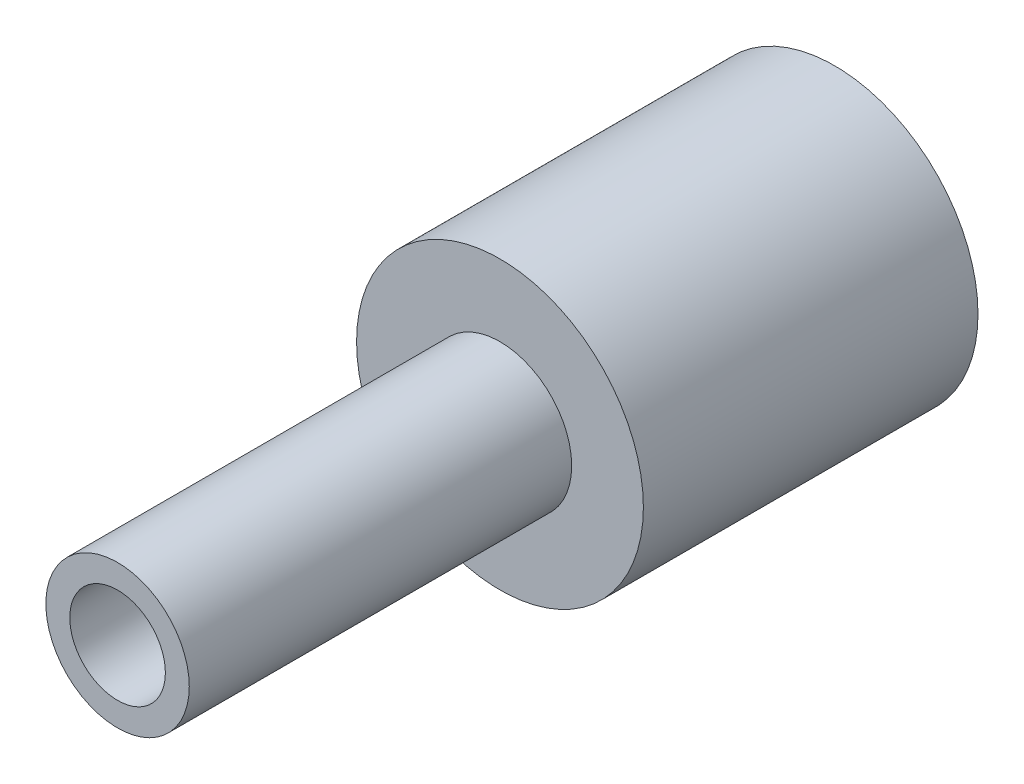
SolidWorks part; units mm, degrees
ref_plane "Front Plane" through (0, 0, 0) normal (0, 0, 1) x (1, 0, 0)
ref_plane "Top Plane" through (0, 0, 0) normal (0, 1, 0) x (1, 0, 0)
ref_plane "Right Plane" through (0, 0, 0) normal (1, 0, 0) x (0, 0, -1)
sketch "Sketch1" plane through (0, 0, 0) normal (0, 0, 1) x (1, 0, 0)
  circle A0 centre (0, 0) radius 38.1
extrude "Boss-Extrude1" add sketch "Sketch1" along normal blind 88.9
sketch "Sketch2" plane through (0, 0, 88.9) normal (0, 0, 1) x (1, 0, 0)
  circle A0 centre (0, 0) radius 19.05
extrude "Boss-Extrude2" add sketch "Sketch2" along normal blind 101.6
sketch "Sketch3" plane through (0, 0, 190.5) normal (0, 0, 1) x (1, 0, 0)
  circle A0 centre (0, 0) radius 12.7
extrude "Cut-Extrude1" cut sketch "Sketch3" against normal blind 202.692
